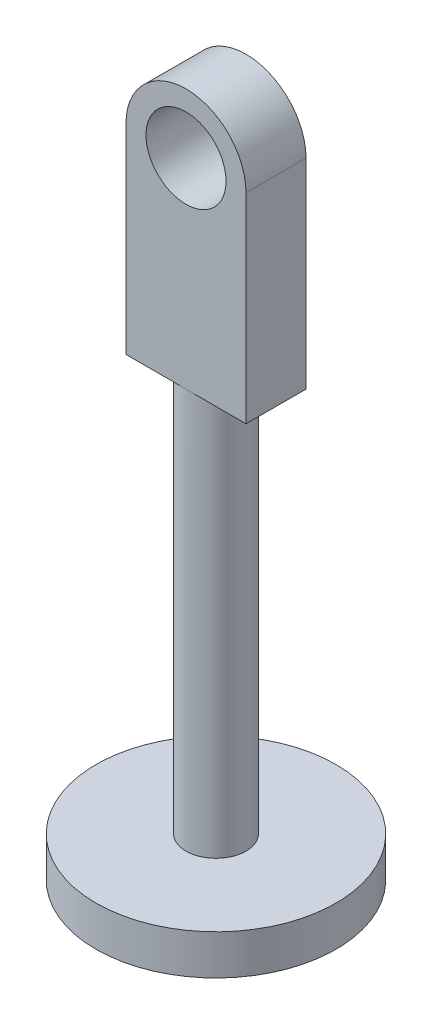
SolidWorks part; units mm, degrees
ref_plane "前视基准面" through (0, 0, 0) normal (0, 0, 1) x (1, 0, 0)
ref_plane "上视基准面" through (0, 0, 0) normal (0, 1, 0) x (1, 0, 0)
ref_plane "右视基准面" through (0, 0, 0) normal (1, 0, 0) x (0, 0, -1)
sketch "草图1" plane through (0, 0, 0) normal (0, 0, 1) x (1, 0, 0)
  line L0 (0, 0) -> (6, 0)
  line L1 (6, 0) -> (6, 10)
  line L2 (0, 0) -> (0, 10)
  arc A0 (6, 10) -> (0, 10) centre (3, 10) ccw
  circle A1 centre (3, 10) radius 2
extrude "凸台-拉伸1" add sketch "草图1" along normal mid plane 3
sketch "草图2" plane through (0, 0, 0) normal (0, -1, 0) x (1, 0, 0)
  line L0 (0, 1.5) -> (6, 1.5) construction
  line L1 (0, 1.5) -> (0, -1.5) construction
  circle A0 centre (3, 0) radius 1.5
  dimension "D1" = 1.5
  dimension "D2" = 3
extrude "凸台-拉伸2" add sketch "草图2" along normal blind 20
sketch "草图3" plane through (0, -20, 0) normal (0, -1, 0) x (1, 0, 0)
  circle A0 centre (3, 0) radius 6
extrude "凸台-拉伸3" add sketch "草图3" along normal blind 2
